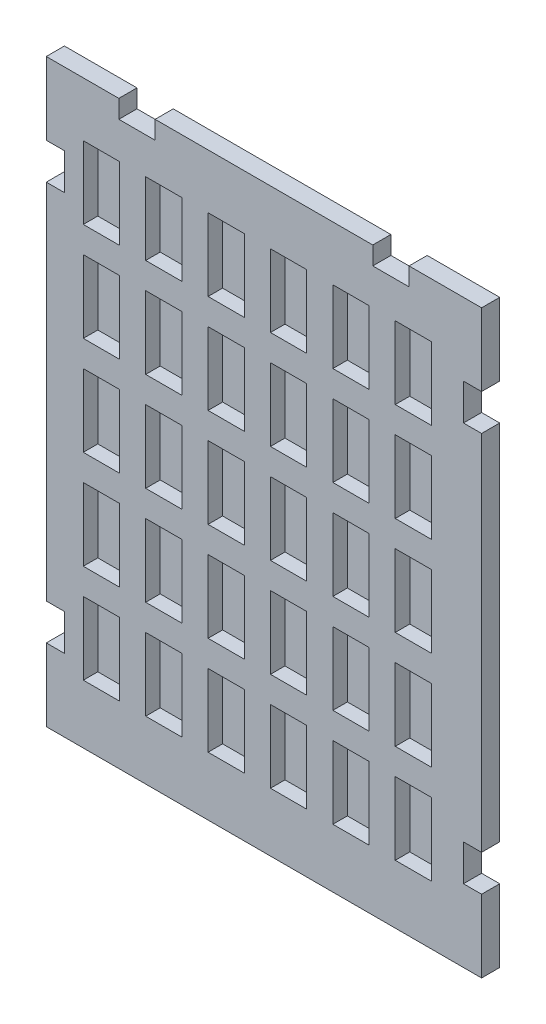
SolidWorks part; units mm, degrees
ref_plane "Front Plane" through (0, 0, 0) normal (0, 0, 1) x (1, 0, 0)
ref_plane "Top Plane" through (0, 0, 0) normal (0, 1, 0) x (1, 0, 0)
ref_plane "Right Plane" through (0, 0, 0) normal (1, 0, 0) x (0, 0, -1)
sketch "Sketch1" plane through (0, 0, 0) normal (0, 0, 1) x (1, 0, 0)
  line L0 (12.7, -101.6) -> (63.5, -101.6)
  line L1 (0, 0) -> (76.2, 0)
  line L2 (0, 0) -> (0, -101.6)
  line L3 (0, -101.6) -> (12.7, -101.6)
  line L4 (76.2, 0) -> (76.2, -101.6)
  line L5 (12.7, 0) -> (19.05, 0)
  line L6 (12.7, 0) -> (12.7, -3.175)
  line L7 (12.7, -3.175) -> (19.05, -3.175)
  line L8 (19.05, 0) -> (19.05, -3.175)
  line L9 (57.15, 0) -> (63.5, 0)
  line L10 (57.15, 0) -> (57.15, -3.175)
  line L11 (57.15, -3.175) -> (63.5, -3.175)
  line L12 (63.5, 0) -> (63.5, -3.175)
  line L13 (76.2, -12.7) -> (73.025, -12.7)
  line L14 (76.2, -12.7) -> (76.2, -19.05)
  line L15 (76.2, -19.05) -> (73.025, -19.05)
  line L16 (73.025, -12.7) -> (73.025, -19.05)
  line L17 (76.2, -82.55) -> (73.025, -82.55)
  line L18 (76.2, -82.55) -> (76.2, -88.9)
  line L19 (76.2, -88.9) -> (73.025, -88.9)
  line L20 (73.025, -82.55) -> (73.025, -88.9)
  line L25 (63.5, -101.6) -> (76.2, -101.6)
  line L29 (0, -88.9) -> (3.175, -88.9)
  line L30 (0, -88.9) -> (0, -82.55)
  line L31 (0, -82.55) -> (3.175, -82.55)
  line L32 (3.175, -88.9) -> (3.175, -82.55)
  line L33 (0, -19.05) -> (3.175, -19.05)
  line L34 (0, -19.05) -> (0, -12.7)
  line L35 (0, -12.7) -> (3.175, -12.7)
  line L36 (3.175, -19.05) -> (3.175, -12.7)
  dimension "D1" = 76.2
  dimension "D2" = 101.6
  dimension "D3" = 12.7
  dimension "D4" = 6.35
  dimension "D5" = 3.175
  dimension "D6" = 6.35
  dimension "D7" = 3.175
  dimension "D8" = 12.7
  dimension "D9" = 12.7
  dimension "D10" = 6.35
  dimension "D11" = 3.175
  dimension "D12" = 3.175
  dimension "D13" = 6.35
  dimension "D14" = 12.7
  dimension "D21" = 3.175
  dimension "D22" = 6.35
  dimension "D23" = 12.7
  dimension "D24" = 12.7
  dimension "D25" = 6.35
  dimension "D26" = 3.175
extrude "Boss-Extrude1" add sketch "Sketch1" along normal blind 3.175
sketch "Sketch2" plane through (0, 0, 3.175) normal (0, 0, 1) x (1, 0, 0)
  line L0 (12.7, -3.175) -> (19.05, -3.175) construction
  line L1 (6.477, -9.525) -> (12.827, -9.525)
  line L2 (6.477, -9.525) -> (6.477, -22.225)
  line L3 (6.477, -22.225) -> (12.827, -22.225)
  line L4 (12.827, -9.525) -> (12.827, -22.225)
  line L5 (6.477, -9.525) -> (12.827, -22.225) construction
  line L6 (6.477, -22.225) -> (12.827, -9.525) construction
  line L7 (3.175, -19.05) -> (3.175, -12.7) construction
  point P0 (9.652, -15.875)
  dimension "D1" = 6.35
  dimension "D2" = 3.302
  dimension "D3" = 6.35
  dimension "D4" = 12.7
extrude "Cut-Extrude1" cut sketch "Sketch2" against normal blind 2.54
pattern_linear "LPattern1" count 6 spacing 10.922 along (1, 0, 0) count 5 spacing 17.272 along (0, -1, 0) of "Cut-Extrude1"
